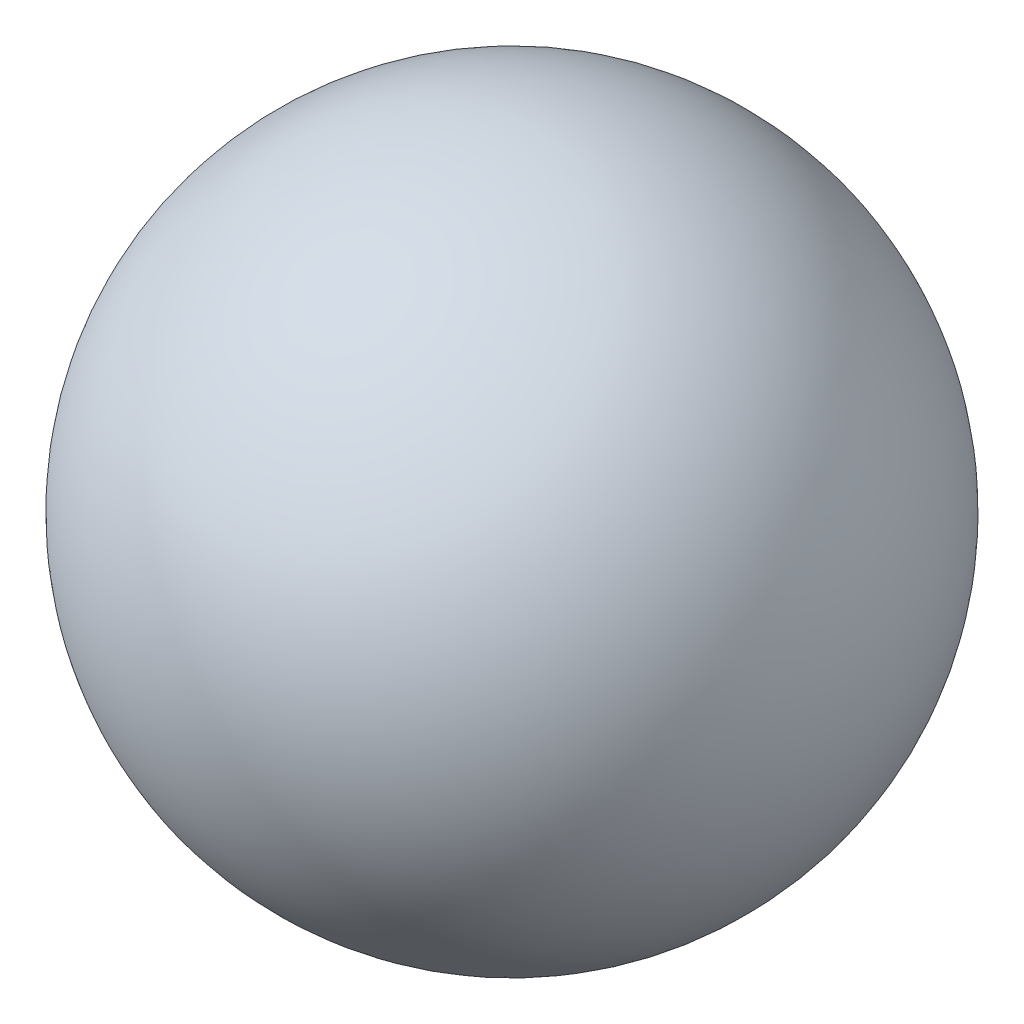
SolidWorks part; units mm, degrees
ref_plane "Front Plane" through (0, 0, 0) normal (0, 0, 1) x (1, 0, 0)
ref_plane "Top Plane" through (0, 0, 0) normal (0, 1, 0) x (1, 0, 0)
ref_plane "Right Plane" through (0, 0, 0) normal (1, 0, 0) x (0, 0, -1)
sketch "Sketch1" plane through (0, 0, 0) normal (0, 1, 0) x (1, 0, 0)
  line L0 (0, 10.16) -> (0, -10.16) construction
  line L1 (0, 10.16) -> (0, -10.16)
  arc A0 (0, -10.16) -> (0, 10.16) centre (0, 0) ccw
revolve "Revolve2" add sketch "Sketch1" angle 360 about L0
